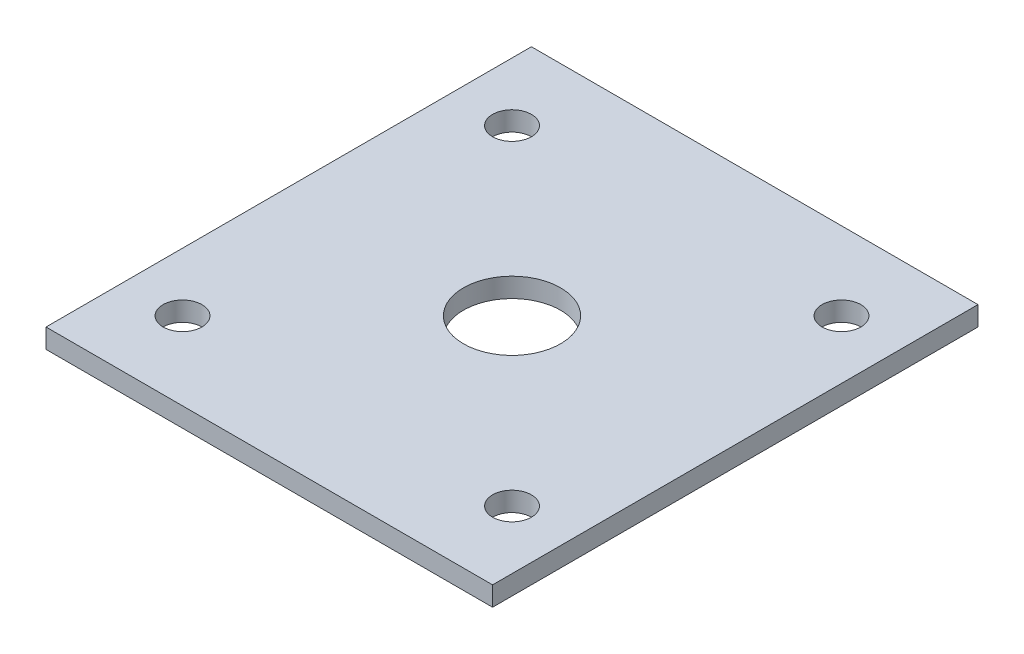
SolidWorks part; units mm, degrees
ref_plane "Front Plane" through (0, 0, 0) normal (0, 0, 1) x (1, 0, 0)
ref_plane "Top Plane" through (0, 0, 0) normal (0, 1, 0) x (1, 0, 0)
ref_plane "Right Plane" through (0, 0, 0) normal (1, 0, 0) x (0, 0, -1)
sketch "Sketch1" plane through (0, 0, 0) normal (0, 1, 0) x (1, 0, 0)
  line L1 (-23, 25) -> (23, 25)
  line L2 (-23, 25) -> (-23, -25)
  line L3 (-23, -25) -> (23, -25)
  line L4 (23, 25) -> (23, -25)
  line L5 (-23, 25) -> (23, -25) construction
  line L6 (-23, -25) -> (23, 25) construction
  point P0 (0, 0)
  dimension "D1" = 46
  dimension "D2" = 50
extrude "Boss-Extrude1" add sketch "Sketch1" along normal blind 2
sketch "Sketch2" plane through (0, 2, 0) normal (0, 1, 0) x (1, 0, 0)
  circle A0 centre (0, 0) radius 5
  dimension "D1" = 10
extrude "Cut-Extrude2" cut sketch "Sketch2" against normal through all contours A0
sketch "Sketch3" plane through (0, 2, 0) normal (0, 1, 0) x (1, 0, 0)
  line L0 (-29.6809, 29.6809) -> (29.6809, -29.6809) construction
  line L1 (-26.2933, -26.2933) -> (26.2933, 26.2933) construction
  line L2 (-23, -25) -> (23, -25) construction
  circle A0 centre (0, 0) radius 24 construction
  circle A1 centre (-16.9693, 16.9693) radius 2
  circle A2 centre (16.9693, 16.9693) radius 2
  circle A3 centre (16.9693, -16.9693) radius 2
  circle A4 centre (-16.9693, -16.9693) radius 2
  point P5 (0, 0)
  point P7 (0, 0)
  point P9 (0, 0)
  point P11 (0, 0)
  dimension "D1" = 48
  dimension "D4" = 4
  dimension "D2" = 90
  dimension "D3" = 45
extrude "Cut-Extrude4" cut sketch "Sketch3" against normal through all
